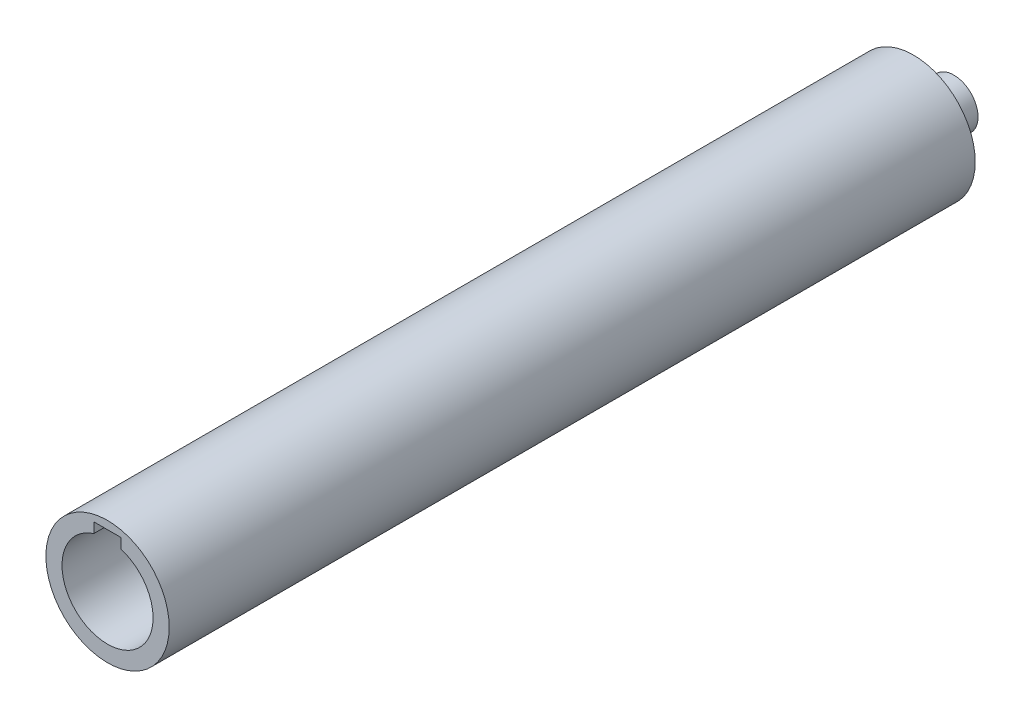
SolidWorks part; units mm, degrees
ref_plane "Front Plane" through (0, 0, 0) normal (0, 0, 1) x (1, 0, 0)
ref_plane "Top Plane" through (0, 0, 0) normal (0, 1, 0) x (1, 0, 0)
ref_plane "Right Plane" through (0, 0, 0) normal (1, 0, 0) x (0, 0, -1)
sketch "Sketch1" plane through (0, 0, 0) normal (0, 0, 1) x (1, 0, 0)
  circle A0 centre (0, 0) radius 38.25
  dimension "56.5" = 76.5
extrude "Boss-Extrude1" add sketch "Sketch1" along normal blind 250
sketch "Sketch3" plane through (0, 0, 250) normal (0, 0, 1) x (1, 0, 0)
  line L0 (-8.5, 26.9409) -> (-8.5, 33.25)
  line L3 (8.5, 33.25) -> (-8.5, 33.25)
  line L7 (8.5, 26.9409) -> (8.5, 33.25)
  arc A0 (-8.5, 26.9409) -> (8.5, 26.9409) centre (0, 0) ccw
  point P10 (0, 28.25)
  dimension "D1" = 56.5
  dimension "D2" = 33.25
  dimension "D3" = 17
extrude "Cut-Extrude2" cut sketch "Sketch3" against normal blind 50
mirror "Mirror1" about plane through (0, 0, 0) normal (0, 0, 1) of "Cut-Extrude2", "Boss-Extrude1"
sketch "Sketch4" plane through (0, 0, -250) normal (0, 0, -1) x (-1, 0, 0)
  circle A0 centre (0, 0) radius 15
  circle A1 centre (0, 0) radius 35
  dimension "D1" = 30
  dimension "D2" = 70
extrude "Boss-Extrude2" add sketch "Sketch4" against normal blind 50
sketch "Sketch5" plane through (0, 0, -200) normal (0, 0, -1) x (-1, 0, 0)
  circle A0 centre (0, 0) radius 15
extrude "Boss-Extrude3" add sketch "Sketch5" along normal blind 75
sketch "Sketch6" plane through (0, 0, 0) normal (1, 0, 0) x (0, 0, -1)
  line L0 (0, 0) -> (-430, 0) construction
  dimension "D1" = 430
